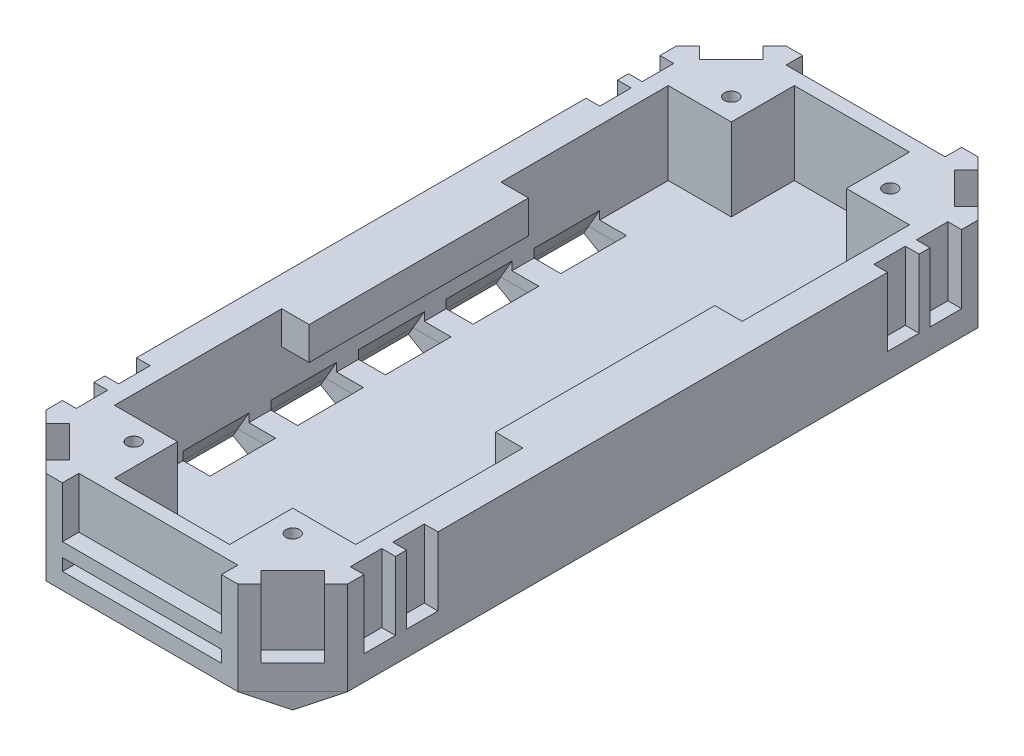
SolidWorks part; units mm, degrees
ref_plane "Front Plane" through (0, 0, 0) normal (0, 0, 1) x (1, 0, 0)
ref_plane "Top Plane" through (0, 0, 0) normal (0, 1, 0) x (1, 0, 0)
ref_plane "Right Plane" through (0, 0, 0) normal (1, 0, 0) x (0, 0, -1)
sketch "Sketch1" plane through (0, 0, 0) normal (0, 1, 0) x (1, 0, 0)
  line L1 (-27.5, -67.5) -> (27.5, -67.5)
  line L2 (-27.5, -67.5) -> (-27.5, 67.5)
  line L3 (-27.5, 67.5) -> (27.5, 67.5)
  line L4 (27.5, -67.5) -> (27.5, 67.5)
  line L5 (-27.5, -67.5) -> (27.5, 67.5) construction
  line L6 (-27.5, 67.5) -> (27.5, -67.5) construction
  point P0 (0, 0)
  dimension "D1" = 135
  dimension "D2" = 55
extrude "Boss-Extrude1" add sketch "Sketch1" along normal blind 17
sketch "Sketch2" plane through (0, 17, 0) normal (0, 1, 0) x (1, 0, 0)
  line L0 (27.5, 67.5) -> (-27.5, 67.5) construction
  line L1 (-10.5, 62) -> (10.5, 62)
  line L2 (-22, 50.5) -> (-22, -50.5)
  line L3 (-10.5, -62) -> (10.5, -62)
  line L4 (22, 50.5) -> (22, -50.5)
  line L5 (-17.7419, 50.5) -> (17.7419, -50.5) construction
  line L6 (-17.7419, -50.5) -> (17.7419, 50.5) construction
  line L7 (27.5, -67.5) -> (27.5, 67.5) construction
  line L8 (0, -9.35) -> (0, 9.35) construction
  line L11 (-22, 50.5) -> (-10.5, 50.5)
  line L12 (-10.5, 62) -> (-10.5, 50.5)
  line L13 (22, 50.5) -> (10.5, 50.5)
  line L14 (10.5, 62) -> (10.5, 50.5)
  line L15 (-9.35, 0) -> (9.35, 0) construction
  line L16 (22, -50.5) -> (10.5, -50.5)
  line L17 (10.5, -62) -> (10.5, -50.5)
  line L18 (-10.5, -62) -> (-10.5, -50.5)
  line L19 (-22, -50.5) -> (-10.5, -50.5)
  point P0 (0, 0)
  dimension "D1" = 5.5
  dimension "D2" = 5.5
  dimension "D3" = 11.5
  dimension "D4" = 11.5
extrude "Cut-Extrude1" cut sketch "Sketch2" against normal blind 15
sketch "Sketch5" plane through (27.5, 0, 0) normal (1, 0, 0) x (0, 0, -1)
  line L0 (67.5, 17) -> (67.5, 0) construction
  line L1 (38, 3) -> (26, 3)
  line L2 (38, 3) -> (38, 7)
  line L3 (38, 7) -> (26, 7)
  line L4 (26, 3) -> (26, 7)
  line L5 (-67.5, 17) -> (67.5, 17) construction
  line L6 (22, 3) -> (22, 7)
  line L7 (22, 3) -> (10, 3)
  line L8 (10, 3) -> (10, 7)
  line L9 (22, 7) -> (10, 7)
  line L10 (6, 3) -> (6, 7)
  line L11 (6, 3) -> (-6, 3)
  line L12 (-6, 3) -> (-6, 7)
  line L13 (6, 7) -> (-6, 7)
  line L14 (-10, 3) -> (-10, 7)
  line L15 (-10, 3) -> (-22, 3)
  line L16 (-22, 3) -> (-22, 7)
  line L17 (-10, 7) -> (-22, 7)
  line L18 (-26, 3) -> (-26, 7)
  line L19 (-26, 3) -> (-38, 3)
  line L20 (-38, 3) -> (-38, 7)
  line L21 (-26, 7) -> (-38, 7)
  dimension "D1" = 12
  dimension "D2" = 29.5
  dimension "D3" = 4
  dimension "D4" = 10
  dimension "D6" = 4
  dimension "D5" = 5
ref_plane "Plane1" through (0, 0, -69.5) normal (0, 0, -1) x (-1, 0, 0)
sketch "Sketch6" plane through (0, 0, 0) normal (0, -1, 0) x (1, 0, 0)
  line L1 (27.5, 67.5) -> (27.5, -67.5) construction
  line L2 (27.5, -67.5) -> (-27.5, -67.5) construction
  line L3 (0, -9.35) -> (0, 9.35) construction
  line L4 (9.35, 0) -> (-9.35, 0) construction
  circle A0 centre (14.5, -54.5) radius 1.25
  circle A1 centre (-14.5, -54.5) radius 1.25
  circle A2 centre (14.5, 54.5) radius 1.25
  circle A3 centre (-14.5, 54.5) radius 1.25
  dimension "D1" = 2.5
  dimension "D2" = 13
  dimension "D3" = 13
sketch "Sketch9" plane through (22, 0, 0) normal (-1, 0, 0) x (0, 0, 1)
  line L0 (50.5, 17) -> (-50.5, 17) construction
  line L1 (20, 17) -> (-20, 17)
  line L2 (20, 17) -> (20, 11)
  line L3 (20, 11) -> (-20, 11)
  line L4 (-20, 17) -> (-20, 11)
  line L5 (0, -9.35) -> (0, 9.35) construction
  point P6 (20, 14)
  dimension "D1" = 20
  dimension "D2" = 40
  dimension "D3" = 6
extrude "Boss-Extrude3" add sketch "Sketch9" along normal blind 5
mirror "Mirror1" about plane through (0, 0, 0) normal (1, 0, 0) of "Boss-Extrude3"
sketch "Sketch11" plane through (0, 0, 67.5) normal (0, 0, 1) x (1, 0, 0)
  line L0 (27.5, 0) -> (14.5096, -7.5)
  line L1 (14.5096, -7.5) -> (10.5096, -7.5)
  line L2 (10.5096, -7.5) -> (10.5096, -10)
  line L3 (10.5096, -10) -> (-4.4904, -10)
  line L4 (-4.4904, -10) -> (-4.4904, 0)
  line L5 (-27.5, 0) -> (27.5, 0) construction
  line L6 (27.5, 0) -> (-4.4904, 0)
  line L7 (0, -9.35) -> (0, 9.35) construction
  line L8 (-27.5, 0) -> (-14.5096, -7.5)
  line L9 (-14.5096, -7.5) -> (-10.5096, -7.5)
  line L10 (-10.5096, -7.5) -> (-10.5096, -10)
  line L11 (-10.5096, -10) -> (4.4904, -10)
  line L12 (4.4904, -10) -> (4.4904, 0)
  line L13 (-27.5, 0) -> (4.4904, 0)
  line M13 (-27.5, 0) -> (27.5, 0)
  dimension "D1" = 30
  dimension "D2" = 4
  dimension "D3" = 15
  dimension "D4" = 10
  dimension "D5" = 2.5
extrude "Boss-Extrude4" add sketch "Sketch11" against normal blind 135 separate body contours L12 L3 L2 L1 L0 L6 | L10 L11 L4 L8 L9 M13 | L3 L12 L4 M13
chamfer "Chamfer2" distance 10 angle 45 4 edges at (27.5, 8.5, -67.5) (-27.5, 8.5, -67.5) (-27.5, 8.5, 67.5) (27.5, 8.5, 67.5)
ref_plane "Plane2" through (30, 0, 0) normal (1, 0, 0) x (0, 0, -1)
sketch "Sketch12" plane through (30, 0, 0) normal (1, 0, 0) x (0, 0, -1)
  line L0 (-67.5, 0) -> (-50.1795, -10)
  line L1 (67.5, -10) -> (-67.5, -10) construction
  line L2 (-50.1795, -10) -> (-67.5, -10)
  line L3 (-67.5, -10) -> (-67.5, 0)
  dimension "D1" = 60
extrude "Cut-Extrude8" cut sketch "Sketch12" against normal blind 80
mirror "Mirror2" about plane through (0, 0, 0) normal (0, 0, 1) of "Cut-Extrude8"
extrude "Cut-Extrude9" cut sketch "Sketch6" against normal through all
sketch "Sketch13" plane through (0, 0, 0) normal (0, 1, 0) x (1, 0, 0)
  line L0 (-27.5, 57.5) -> (-27.5, 67.5)
  line L1 (-27.5, 67.5) -> (-17.5, 67.5)
  line L2 (-17.5, 67.5) -> (-27.5, 57.5)
  line L3 (0, -9.35) -> (0, 9.35) construction
  line L4 (27.5, 67.5) -> (17.5, 67.5)
  line L5 (27.5, 57.5) -> (27.5, 67.5)
  line L6 (17.5, 67.5) -> (27.5, 57.5)
  line L7 (-9.35, 0) -> (9.35, 0) construction
  line L8 (27.5, -57.5) -> (27.5, -67.5)
  line L9 (17.5, -67.5) -> (27.5, -57.5)
  line L10 (27.5, -67.5) -> (17.5, -67.5)
  line L11 (-27.5, -67.5) -> (-17.5, -67.5)
  line L12 (-27.5, -57.5) -> (-27.5, -67.5)
  line L13 (-17.5, -67.5) -> (-27.5, -57.5)
extrude "Cut-Extrude10" cut sketch "Sketch13" against normal through all
sketch "Sketch14" plane through (-10.5096, 0, 0) normal (-1, 0, 0) x (0, 0, 1)
  line L0 (0, -9.35) -> (0, 9.35) construction
  line L1 (32.5, -10.0514) -> (-32.5, -10.0514)
  line L2 (32.5, -10.0514) -> (32.5, -7.5)
  line L3 (32.5, -7.5) -> (-32.5, -7.5)
  line L4 (-32.5, -10.0514) -> (-32.5, -7.5)
  line L5 (32.5, -10.0514) -> (-32.5, -7.5) construction
  line L6 (32.5, -7.5) -> (-32.5, -10.0514) construction
  line L7 (-54.5096, -7.5) -> (54.5096, -7.5) construction
  point P0 (0, -8.7757)
  dimension "D1" = 65
extrude "Cut-Extrude11" cut sketch "Sketch14" against normal through all
sketch "Sketch15" plane through (0, 0, 67.5) normal (0, 0, 1) x (1, 0, 0)
  line L0 (-17.5, 17) -> (17.5, 17) construction
  line L1 (14.5, 17) -> (-14.5, 17)
  line L2 (14.5, 17) -> (14.5, 7.6995)
  line L3 (14.5, 3) -> (-14.5, 3)
  line L4 (-14.5, 17) -> (-14.5, 7.6995)
  line L5 (14.5, 17) -> (-14.5, 3) construction
  line L6 (14.5, 3) -> (-14.5, 17) construction
  line L7 (-17.5, 0) -> (17.5, 0) construction
  line L8 (-17.5, 17) -> (-17.5, 0) construction
  line L9 (17.5, 0) -> (17.5, 17) construction
  line L10 (14.5, 5.1995) -> (14.5, 3)
  line L11 (14.5, 5.1995) -> (-14.5, 5.1995)
  line L13 (14.5, 7.6995) -> (-14.5, 7.6995)
  line L15 (14.5, 5.1995) -> (8.9534, 5.6777) construction
  line L16 (14.5, 7.6995) -> (6.2403, 6.9875) construction
  line L17 (-14.5, 5.1995) -> (-14.5, 3)
  line L18 (0, 6.4495) -> (-14.5, 5.1995) construction
  line L19 (0, 6.4495) -> (-14.5, 7.6995) construction
  point P0 (0, 10)
  point P13 (0, 6.4495)
  dimension "D1" = 0
  dimension "D2" = 3
  dimension "D3" = 3
  dimension "D4" = 3
  dimension "D5" = 2.5
sketch "Sketch16" plane through (-42.5, 0, 42.5) normal (-0.7071, 0, 0.7071) x (0.7071, 0, 0.7071)
  line L0 (21.2132, 17) -> (35.3553, 17) construction
  line L1 (32.3553, 17) -> (24.2132, 17)
  line L2 (32.3553, 17) -> (32.3553, 4.5)
  line L3 (32.3553, 4.5) -> (24.2132, 4.5)
  line L4 (24.2132, 17) -> (24.2132, 4.5)
  line L5 (32.3553, 17) -> (24.2132, 4.5) construction
  line L6 (32.3553, 4.5) -> (24.2132, 17) construction
  line L7 (35.3553, 0) -> (21.2132, 0) construction
  line L8 (35.3553, 17) -> (35.3553, 0) construction
  line L9 (21.2132, 0) -> (21.2132, 17) construction
  point P0 (28.2843, 10.75)
  point P7 (28.2843, 4.5)
  dimension "D1" = 0
  dimension "D2" = 4.5
  dimension "D3" = 3
  dimension "D4" = 3
extrude "Cut-Extrude12" cut sketch "Sketch15" against normal blind 3
extrude "Cut-Extrude13" cut sketch "Sketch16" against normal blind 3
mirror "Mirror4" about plane through (0, 0, 0) normal (1, 0, 0) of "Cut-Extrude13"
mirror "Mirror5" about plane through (0, 0, 0) normal (0, 0, 1) of "Mirror4", "Cut-Extrude13", "Cut-Extrude12"
sketch "Sketch19" plane through (-27.5, 0, 0) normal (-1, 0, 0) x (0, 0, 1)
  line L0 (-57.5, 17) -> (57.5, 17) construction
  line L1 (54.5, 4.5) -> (48.75, 4.5)
  line L2 (54.5, 4.5) -> (54.5, 17)
  line L3 (54.5, 17) -> (48.75, 17)
  line L4 (48.75, 4.5) -> (48.75, 17)
  line L6 (41, 4.5) -> (46.75, 4.5)
  line L7 (41, 4.5) -> (41, 17)
  line L8 (41, 17) -> (46.75, 17)
  line L9 (46.75, 4.5) -> (46.75, 17)
  line L12 (57.5, 0) -> (57.5, 17) construction
  line L13 (-57.5, 0) -> (57.5, 0) construction
  point P10 (46.75, 10.75)
  point P11 (54.5, 10.75)
  dimension "D1" = 2
  dimension "D2" = 5.75
  dimension "D3" = 3
  dimension "D4" = 5.75
  dimension "D5" = 4.5
  dimension "D6" = 4.5
extrude "Cut-Extrude14" cut sketch "Sketch19" against normal blind 2.5
mirror "Mirror6" about plane through (0, 0, 0) normal (0, 0, 1) of "Cut-Extrude14"
mirror "Mirror7" about plane through (0, 0, 0) normal (1, 0, 0) of "Mirror6", "Cut-Extrude14"
sketch "Sketch20" plane through (-6.875, -11.9078, 0) normal (-0.5, -0.866, 0) x (0.866, -0.5, 0)
  line L0 (-32.3157, 41) -> (-26.0657, 41) construction
  line L1 (-15.8157, 38) -> (-20.8157, 38)
  line L3 (-15.8157, 26) -> (-20.8157, 26)
  line L4 (-20.8157, 38) -> (-20.8157, 26)
  line L5 (-23.8157, -57.5) -> (-23.8157, 57.5) construction
  line L6 (-15.8157, 38) -> (-15.8157, 26)
  line L7 (-15.8157, 22) -> (-20.8157, 22)
  line L8 (-20.8157, 22) -> (-20.8157, 10)
  line L9 (-15.8157, 10) -> (-20.8157, 10)
  line L10 (-15.8157, 22) -> (-15.8157, 10)
  line L11 (-15.8157, 6) -> (-20.8157, 6)
  line L12 (-20.8157, 6) -> (-20.8157, -6)
  line L13 (-15.8157, -6) -> (-20.8157, -6)
  line L14 (-15.8157, 6) -> (-15.8157, -6)
  line L15 (-15.8157, -10) -> (-20.8157, -10)
  line L16 (-20.8157, -10) -> (-20.8157, -22)
  line L17 (-15.8157, -22) -> (-20.8157, -22)
  line L18 (-15.8157, -10) -> (-15.8157, -22)
  line L19 (-15.8157, -26) -> (-20.8157, -26)
  line L20 (-20.8157, -26) -> (-20.8157, -38)
  line L21 (-15.8157, -38) -> (-20.8157, -38)
  line L22 (-15.8157, -26) -> (-15.8157, -38)
  line L23 (-32.3157, -57.5) -> (-23.8157, -57.5) construction
  point P2 (-18.3157, -38)
  dimension "D1" = 3
  dimension "D2" = 5
  dimension "D3" = 3
  dimension "D4" = 5
  dimension "D5" = 19.5
extrude "Cut-Extrude15" cut sketch "Sketch20" against normal blind 8
mirror "Mirror8" about plane through (0, 0, 0) normal (1, 0, 0) of "Cut-Extrude15"
sketch "Sketch21" plane through (0, -29.2284, -16.875) normal (0, -0.866, -0.5) x (1, 0, 0)
  line L0 (22.5, -52.6832) -> (22.5, -54.1266)
  line L1 (17.5, -58.4567) -> (27.5, -49.7965) construction
  line L2 (22.5, -54.1266) -> (17.5, -58.4567)
  line L3 (17.5, -58.4567) -> (22.5, -52.6832)
